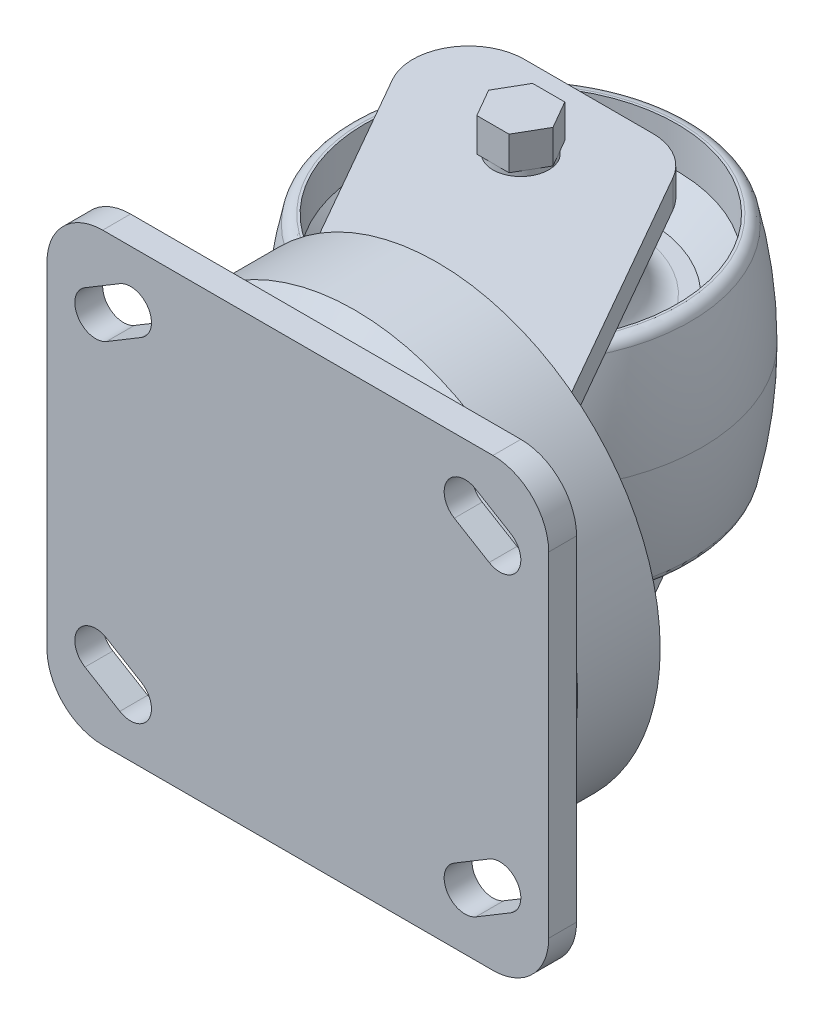
SolidWorks part; units mm, degrees
ref_plane "Front" through (0, 0, 0) normal (0, 0, 1) x (1, 0, 0)
ref_plane "Top" through (0, 0, 0) normal (0, 1, 0) x (1, 0, 0)
ref_plane "Right" through (0, 0, 0) normal (1, 0, 0) x (0, 0, -1)
sketch "Sketch1" plane through (0, 0, 0) normal (0, 0, 1) x (1, 0, 0)
  line L0 (0, 19.05) -> (0, 0) construction
  line L1 (-19.05, 0) -> (0, 0) construction
  line L2 (0, 0) -> (0, -30.1625)
  line L3 (0, -30.1625) -> (19.05, -30.1625)
  line L4 (19.05, -30.1625) -> (19.05, -15.875)
  line L5 (25.4, -9.525) -> (28.9844, -9.525)
  line L6 (35.56, -16.1006) -> (35.56, -25.4)
  line L7 (35.56, -25.4) -> (38.1, -25.4)
  line L8 (25.4, 0) -> (25.4, -9.525) construction
  line L9 (41.275, 0) -> (0, 0)
  line L10 (25.4, -9.525) -> (25.4, -30.9245) construction
  line L11 (65.7028, -30.9245) -> (-14.9028, -30.9245) construction
  line L12 (0, -30.9245) -> (0, -30.1625) construction
  line L13 (-14.9028, -30.9245) -> (0, -30.9245) construction
  line L14 (-9.1145, -37.2745) -> (59.9145, -37.2745) construction
  line L15 (28.9844, -9.525) -> (35.56, -16.1006)
  arc A0 (41.275, 0) -> (38.1, -25.4) centre (-61.9125, 0) cw
  circle A1 centre (25.4, 0) radius 50.8 construction
  arc A2 (25.4, -9.525) -> (19.05, -15.875) centre (25.4, -15.875) ccw
  dimension "D2" = 9.525
  dimension "Plate Width" = 101.6
  dimension "D7" = 6.35
  dimension "D1" = 0.762
  dimension "Wheel Dia" = 82.55
  dimension "Wheel Width" = 50.8
  dimension "D3" = 3.175
  dimension "D4" = 60.325
  dimension "D6" = 38.1
  dimension "D8" = 135
  dimension "Swivel Lead" = 25.4
  dimension "Leg Thickness" = 6.35
  dimension "Wheel Thickness" = 2.54
revolve "Revolve1" add sketch "Sketch1" angle 360 about L0
fillet "Fillet4" radius 2.54 1 edges at (-38.1, -25.4, 0)
chamfer "Chamfer1" distance 1.524 angle 45 1 edges at (-19.05, -30.1625, 0)
ref_plane "Plane1" through (0, -30.9245, 0) normal (0, -1, 0) x (1, 0, 0)
sketch "Sketch3" plane through (0, -30.9245, 0) normal (0, -1, 0) x (1, 0, 0)
  line L0 (-40.1402, -19.05) -> (-3.8545, 44.45)
  line L1 (-3.8545, 50.8) -> (54.6545, 50.8) construction
  line L2 (54.6545, 44.45) -> (18.3688, -19.05)
  line L3 (25.4, 50.8) -> (25.4, 69.85) construction
  line L4 (54.6545, 44.45) -> (-3.8545, 44.45)
  line L5 (54.6545, 44.45) -> (54.6545, 50.8) construction
  line L6 (-3.8545, 50.8) -> (-3.8545, 44.45) construction
  line L7 (25.4, 0) -> (25.4, 50.8) construction
  line L8 (-31.75, 76.2) -> (82.55, 76.2) construction
  line L9 (-31.75, 76.2) -> (-31.75, 69.85) construction
  line L10 (-31.75, 69.85) -> (82.55, 69.85) construction
  line L11 (82.55, 76.2) -> (82.55, 69.85) construction
  line L12 (18.3688, -19.05) -> (-40.1402, -19.05)
  line L14 (0, 0) -> (25.4, 44.45) construction
  circle A2 centre (0, 0) radius 41.275 construction
  circle A3 centre (0, 0) radius 19.05 construction
  point P11 (25.4, 50.8)
  point P18 (25.4, 69.85)
  dimension "D1" = 50.8
  dimension "D3" = 19.05
  dimension "Overall Height" = 117.475
  dimension "Plate Thickness" = 6.35
  dimension "Plate Length" = 114.3
extrude "Extrude1" add sketch "Sketch3" along normal blind 6.35 separate body
fillet "Fillet5" radius 12.7 2 edges at (18.3688, -34.0995, -19.05) (-40.1402, -34.0995, -19.05)
sketch "Sketch7" plane through (0, 0, 0) normal (0, 1, 0) x (1, 0, 0)
  line L1 (-31.75, -76.2) -> (82.55, -76.2)
  line L2 (-31.75, -76.2) -> (-31.75, -69.85)
  line L3 (-31.75, -69.85) -> (82.55, -69.85)
  line L4 (82.55, -76.2) -> (82.55, -69.85)
extrude "Extrude2" add sketch "Sketch7" against normal blind 50.8 separate body
sketch "Sketch20" plane through (0, 0, 44.45) normal (0, 0, 1) x (1, 0, 0)
  line L0 (-25.4, 0) -> (76.2, 0)
  circle A0 centre (25.4, 0) radius 50.8 construction
  arc A1 (-25.4, 0) -> (76.2, 0) centre (25.4, 0) ccw
extrude "Extrude8" add sketch "Sketch20" along normal up to vertex (6.35 mm away) up to point (25.4, -30.9245, 50.8)
sketch "Sketch8" plane through (0, 0, 50.8) normal (0, 0, 1) x (1, 0, 0)
  line L0 (-25.4, 0) -> (-6.35, 0)
  line L1 (57.15, 0) -> (76.2, 0)
  arc A0 (-6.35, 0) -> (57.15, 0) centre (25.4, 0) ccw
  arc A1 (-25.4, 0) -> (76.2, 0) centre (25.4, 0) ccw
  circle A4 centre (25.4, 0) radius 50.8 construction
  dimension "D1" = 19.05
extrude "Extrude3" add sketch "Sketch8" along normal offset from surface (17.526 mm away) 1.524 up to face at (25.4, -25.4, 69.85)
chamfer "Chamfer2" distance 5.08 angle 45 1 edges at (25.4, -50.8, 68.326)
sketch "Sketch9" plane through (0, 0, 69.85) normal (0, 0, -1) x (-1, 0, 0)
  line L0 (25.4, 0) -> (6.35, 0) construction
  line L1 (-25.4, -31.75) -> (-25.4, -25.4) construction
  line L3 (-50.8, 0) -> (-31.75, 0)
  line L4 (-19.05, 0) -> (0, 0)
  arc A0 (-50.8, 0) -> (0, 0) centre (-25.4, 0) ccw
  arc A1 (-31.75, 0) -> (-19.05, 0) centre (-25.4, 0) ccw
  arc A3 (-57.15, 0) -> (6.35, 0) centre (-25.4, 0) ccw construction
  arc A4 (-57.15, 0) -> (6.35, 0) centre (-25.4, 0) ccw construction
  dimension "D1" = 6.35
extrude "Extrude4" add sketch "Sketch9" along normal offset from surface (17.78 mm away) 1.27 up to face at (57.15, 0, 50.8)
chamfer "Chamfer3" distance 5.08 angle 45 1 edges
sketch "Sketch10" plane through (0, 0, 76.2) normal (0, 0, 1) x (1, 0, 0)
  line L0 (25.4, 0) -> (25.4, -50.8) construction
  line L1 (-18.1872, -29.2537) -> (-10.2497, -34.0162)
  line L2 (82.55, -50.8) -> (-31.75, -50.8) construction
  line L3 (-23.0878, -37.4213) -> (-15.1503, -42.1838)
  line L4 (65.9503, -42.1838) -> (73.8878, -37.4213)
  line L5 (0, 0) -> (25.4, 0) construction
  line L6 (41.275, 0) -> (-41.275, 0) construction
  line L7 (68.9872, -29.2537) -> (61.0497, -34.0162)
  arc A0 (-15.1503, -42.1838) -> (-10.2497, -34.0162) centre (-12.7, -38.1) ccw
  arc A1 (-18.1872, -29.2537) -> (-23.0878, -37.4213) centre (-20.6375, -33.3375) ccw
  arc A2 (68.9872, -29.2537) -> (73.8878, -37.4213) centre (71.4375, -33.3375) cw
  arc A3 (61.0497, -34.0162) -> (65.9503, -42.1838) centre (63.5, -38.1) ccw
  dimension "D1" = 9.525
  dimension "D2" = 76.2
  dimension "D3" = 76.2
  dimension "D4" = 66.675
  dimension "D5" = 92.075
extrude "Cut-Extrude1" cut sketch "Sketch10" against normal up to next (6.35 mm away)
fillet "Fillet1" radius 12.7 2 edges at (82.55, -50.8, 73.025) (-31.75, -50.8, 73.025)
sketch "Sketch11" plane through (0, -30.9245, 0) normal (0, 1, 0) x (-1, 0, 0)
  line L0 (0, 16.5894) -> (0, -16.5894) construction
  line L1 (16.5894, 0) -> (-16.5894, 0) construction
  circle A0 centre (0, 0) radius 6.35
  dimension "D1" = 12.7
extrude "Cut-Extrude2" cut sketch "Sketch11" against normal through all and the other way through all
sketch "Sketch12" plane through (0, 0, 0) normal (0, 1, 0) x (-1, 0, 0)
  line L0 (0, 6.3246) -> (0, 6.35) construction
  circle A0 centre (0, 0) radius 6.3246
  circle A2 centre (0, 0) radius 6.35 construction
  circle A3 centre (0, 0) radius 6.35 construction
  dimension "D1" = 0.0254
extrude "Extrude5" add sketch "Sketch12" against normal offset from surface (38.5445 mm away) 1.27 separate body up to face at (-6.35, -37.2745, 0) offset beyond the face yes
sketch "Sketch13" plane through (0, -38.5445, 0) normal (0, -1, 0) x (1, 0, 0)
  line L1 (3.6662, 6.35) -> (-3.6662, 6.35)
  line L2 (-3.6662, 6.35) -> (-7.3323, 0)
  line L3 (-7.3323, 0) -> (-3.6662, -6.35)
  line L4 (-3.6662, -6.35) -> (3.6662, -6.35)
  line L5 (3.6662, -6.35) -> (7.3323, 0)
  line L6 (7.3323, 0) -> (3.6662, 6.35)
  circle A0 centre (0, 0) radius 6.35 construction
  circle A1 centre (0, 0) radius 6.35 construction
  circle A2 centre (0, 0) radius 6.3246 construction
extrude "Extrude6" add sketch "Sketch13" along normal blind 7.62
mirror "Mirror1" about plane through (0, 0, 0) normal (0, 1, 0) of bodies 115 116 117 119 108
split line "Split Line1"
equation "\"D4@Sketch1\"=\"Wheel Width@Sketch1\"+.375"
equation "\"Plate Width@Extrude2\"=\"Plate Width@Sketch1\"/2"
equation "\"D2@Extrude1\"=\"Leg Thickness@Sketch1\""
